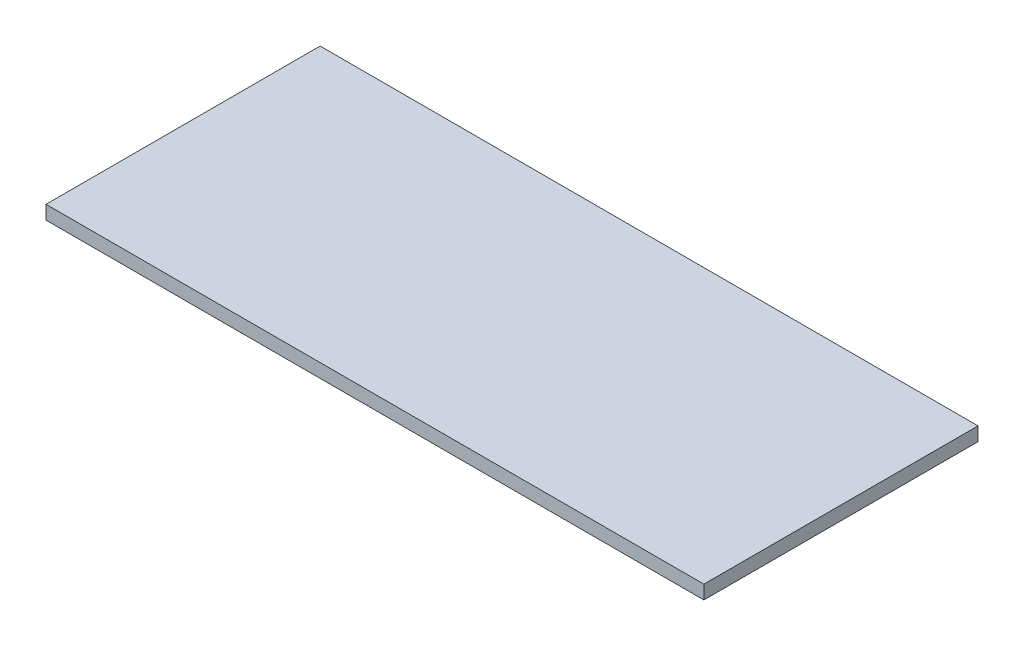
SolidWorks part; units mm, degrees
ref_plane "Front Plane" through (0, 0, 0) normal (0, 0, 1) x (1, 0, 0)
ref_plane "Top Plane" through (0, 0, 0) normal (0, 1, 0) x (1, 0, 0)
ref_plane "Right Plane" through (0, 0, 0) normal (1, 0, 0) x (0, 0, -1)
sketch "Sketch1" plane through (0, 0, 0) normal (0, 0, 1) x (1, 0, 0)
  line L5 (0, 0) -> (240, 0)
  line L6 (0, 0) -> (0, 5)
  line L7 (0, 5) -> (240, 5)
  line L8 (240, 0) -> (240, 5)
  dimension "D1" = 240
  dimension "D2" = 5
extrude "Boss-Extrude1" add sketch "Sketch1" along normal blind 100 contours L5 L8 L7 L6
